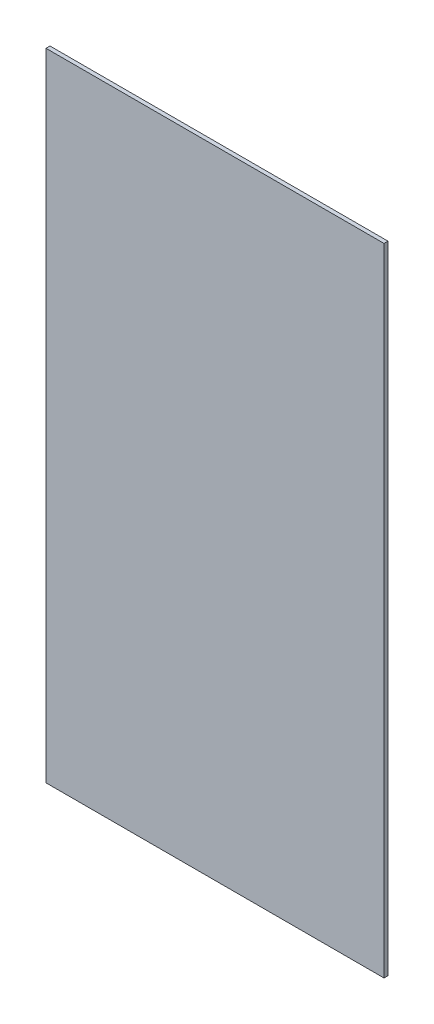
SolidWorks part; units mm, degrees
ref_plane "Alzado" through (0, 0, 0) normal (0, 0, 1) x (1, 0, 0)
ref_plane "Planta" through (0, 0, 0) normal (0, 1, 0) x (1, 0, 0)
ref_plane "Vista lateral" through (0, 0, 0) normal (1, 0, 0) x (0, 0, -1)
sketch "Croquis1" plane through (0, 0, 0) normal (0, 0, 1) x (1, 0, 0)
  line L1 (-85, -160) -> (85, -160)
  line L2 (-85, -160) -> (-85, 160)
  line L3 (-85, 160) -> (85, 160)
  line L4 (85, -160) -> (85, 160)
  line L5 (-85, -160) -> (85, 160) construction
  line L6 (-85, 160) -> (85, -160) construction
  point P0 (0, 0)
  dimension "D1" = 170
  dimension "D2" = 320
extrude "Saliente-Extruir1" add sketch "Croquis1" along normal blind 2
sketch "Croquis2" plane through (0, 0, 2) normal (0, 0, 1) x (1, 0, 0)
  line L0 (-85, 160) -> (85, -160) construction
  line L1 (85, 0) -> (-85, 0) construction
  line L2 (-85, -160) -> (85, 160) construction
  line L3 (-85, 160) -> (-85, -160) construction
  point P14 (0, 0)
